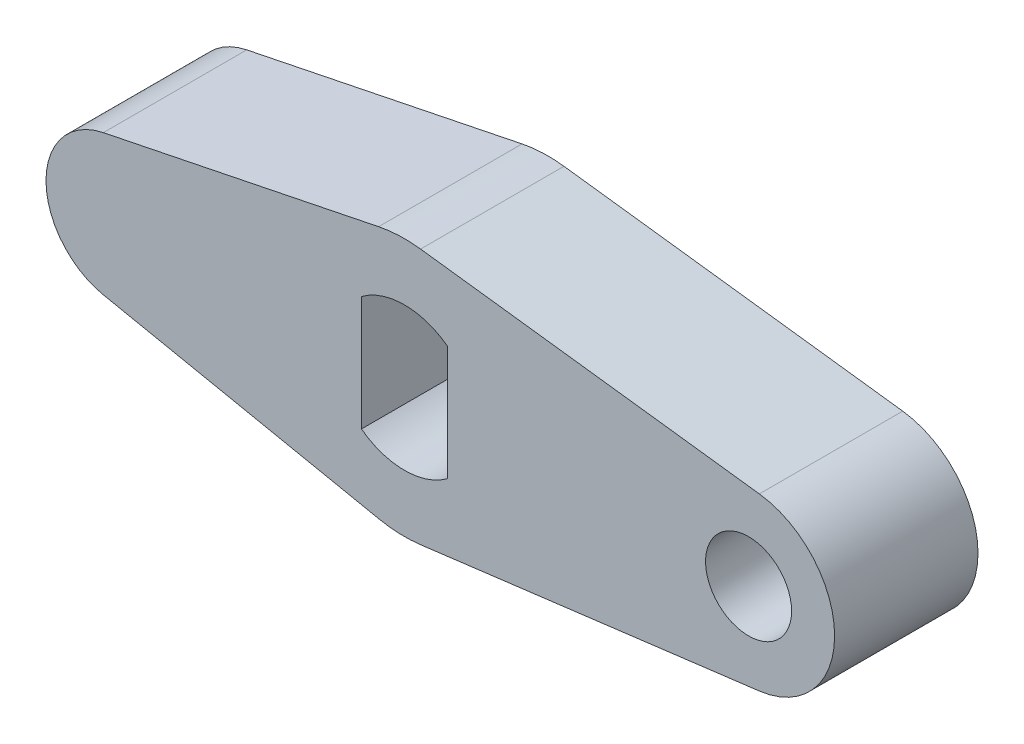
SolidWorks part; units mm, degrees
ref_plane "Front" through (0, 0, 0) normal (0, 0, 1) x (1, 0, 0)
ref_plane "Top" through (0, 0, 0) normal (0, 1, 0) x (1, 0, 0)
ref_plane "Right" through (0, 0, 0) normal (1, 0, 0) x (0, 0, -1)
sketch "Эскиз1" plane through (0, 0, 0) normal (0, 0, 1) x (1, 0, 0)
  line L0 (-20.294, 0) -> (-7.5, 0) construction
  line L1 (-0.9, 4.4091) -> (-10.5, 2.4495)
  line L2 (-0.9, -4.4091) -> (-10.5, -2.4495)
  line L3 (0.5625, 4.4647) -> (12.375, 2.9765)
  line L4 (0.5625, -4.4647) -> (12.375, -2.9765)
  line L5 (-1.5, 2) -> (-1.5, -2)
  line L6 (1.5, 2) -> (1.5, -2)
  line L7 (-4.5, 0) -> (26.9723, 0) construction
  circle A0 centre (0, 0) radius 2.5
  circle A1 centre (0, 0) radius 4.5
  circle A2 centre (12, 0) radius 1.5
  circle A3 centre (-10, 0) radius 2.5
  circle A4 centre (12, 0) radius 3
  dimension "D1" = 5
  dimension "D2" = 9
  dimension "D3" = 3
  dimension "D5" = 5
  dimension "D7" = 6
  dimension "D4" = 12
  dimension "D6" = 10
  dimension "D8" = 3
extrude "Бобышка-Вытянуть1" add sketch "Эскиз1" along normal mid plane 5 contours A3 L2 A1 L1 | A3 | A1 A0 | A4 L3 A1 L4 | A4 A2 | L5 A0 | L6 A0
